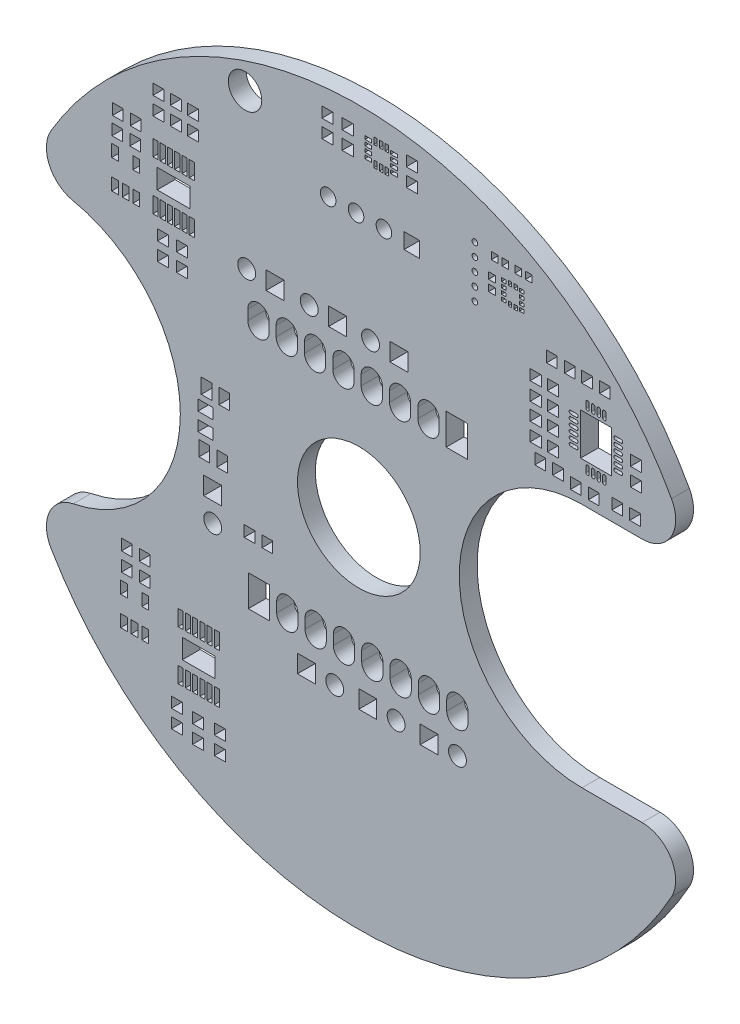
SolidWorks part; units mm, degrees
ref_plane "Plan de face" through (0, 0, 0) normal (0, 0, 1) x (1, 0, 0)
ref_plane "Plan de dessus" through (0, 0, 0) normal (0, 1, 0) x (1, 0, 0)
ref_plane "Plan de droite" through (0, 0, 0) normal (1, 0, 0) x (0, 0, -1)
sketch "Model" plane through (0, 0, 0) normal (0, 0, 1) x (1, 0, 0)
  line L0 (14.8, 23.5) -> (14.8, 23.2)
  line L1 (14.8, 23.2) -> (14.4, 23.2)
  line L2 (14.4, 23.2) -> (14.4, 23.5)
  line L3 (14.4, 23.5) -> (14.8, 23.5)
  line L4 (14.8, 24) -> (14.8, 23.7)
  line L5 (14.8, 23.7) -> (14.4, 23.7)
  line L6 (14.4, 23.7) -> (14.4, 24)
  line L7 (14.4, 24) -> (14.8, 24)
  line L8 (14.8, 24.5) -> (14.8, 24.2)
  line L9 (14.8, 24.2) -> (14.4, 24.2)
  line L10 (14.4, 24.2) -> (14.4, 24.5)
  line L11 (14.4, 24.5) -> (14.8, 24.5)
  line L12 (14.8, 25) -> (14.8, 24.7)
  line L13 (14.8, 24.7) -> (14.4, 24.7)
  line L14 (14.4, 24.7) -> (14.4, 25)
  line L15 (14.4, 25) -> (14.8, 25)
  line L16 (13.9, 25.1) -> (14.2, 25.1)
  line L17 (14.2, 25.1) -> (14.2, 24.7)
  line L18 (14.2, 24.7) -> (13.9, 24.7)
  line L19 (13.9, 24.7) -> (13.9, 25.1)
  line L20 (13.4, 25.1) -> (13.7, 25.1)
  line L21 (13.7, 25.1) -> (13.7, 24.7)
  line L22 (13.7, 24.7) -> (13.4, 24.7)
  line L23 (13.4, 24.7) -> (13.4, 25.1)
  line L24 (13.2, 25) -> (13.2, 24.7)
  line L25 (13.2, 24.7) -> (12.8, 24.7)
  line L26 (12.8, 24.7) -> (12.8, 25)
  line L27 (12.8, 25) -> (13.2, 25)
  line L28 (13.2, 24.5) -> (13.2, 24.2)
  line L29 (13.2, 24.2) -> (12.8, 24.2)
  line L30 (12.8, 24.2) -> (12.8, 24.5)
  line L31 (12.8, 24.5) -> (13.2, 24.5)
  line L32 (13.2, 24) -> (13.2, 23.7)
  line L33 (13.2, 23.7) -> (12.8, 23.7)
  line L34 (12.8, 23.7) -> (12.8, 24)
  line L35 (12.8, 24) -> (13.2, 24)
  line L36 (13.2, 23.5) -> (13.2, 23.2)
  line L37 (13.2, 23.2) -> (12.8, 23.2)
  line L38 (12.8, 23.2) -> (12.8, 23.5)
  line L39 (12.8, 23.5) -> (13.2, 23.5)
  line L40 (13.4, 23.5) -> (13.7, 23.5)
  line L41 (13.7, 23.5) -> (13.7, 23.1)
  line L42 (13.7, 23.1) -> (13.4, 23.1)
  line L43 (13.4, 23.1) -> (13.4, 23.5)
  line L44 (13.9, 23.5) -> (14.2, 23.5)
  line L45 (14.2, 23.5) -> (14.2, 23.1)
  line L46 (14.2, 23.1) -> (13.9, 23.1)
  line L47 (13.9, 23.1) -> (13.9, 23.5)
  line L48 (14.565, 25.93) -> (13.975, 25.93)
  line L49 (13.975, 25.93) -> (13.975, 26.57)
  line L50 (13.975, 26.57) -> (14.565, 26.57)
  line L51 (14.565, 26.57) -> (14.565, 25.93)
  line L52 (15.525, 25.93) -> (14.935, 25.93)
  line L53 (14.935, 25.93) -> (14.935, 26.57)
  line L54 (14.935, 26.57) -> (15.525, 26.57)
  line L55 (15.525, 26.57) -> (15.525, 25.93)
  line L56 (12.835, 26.57) -> (13.425, 26.57)
  line L57 (13.425, 26.57) -> (13.425, 25.93)
  line L58 (13.425, 25.93) -> (12.835, 25.93)
  line L59 (12.835, 25.93) -> (12.835, 26.57)
  line L60 (11.875, 26.57) -> (12.465, 26.57)
  line L61 (12.465, 26.57) -> (12.465, 25.93)
  line L62 (12.465, 25.93) -> (11.875, 25.93)
  line L63 (11.875, 25.93) -> (11.875, 26.57)
  line L64 (11.63, 24.285) -> (11.63, 24.875)
  line L65 (11.63, 24.875) -> (12.27, 24.875)
  line L66 (12.27, 24.875) -> (12.27, 24.285)
  line L67 (12.27, 24.285) -> (11.63, 24.285)
  line L68 (11.63, 23.325) -> (11.63, 23.915)
  line L69 (11.63, 23.915) -> (12.27, 23.915)
  line L70 (12.27, 23.915) -> (12.27, 23.325)
  line L71 (12.27, 23.325) -> (11.63, 23.325)
  line L72 (-12.725, -1.125) -> (-11.775, -1.125)
  line L73 (-11.775, -1.125) -> (-11.775, -2.475)
  line L74 (-11.775, -2.475) -> (-12.725, -2.475)
  line L75 (-12.725, -2.475) -> (-12.725, -1.125)
  line L76 (-14.325, -1.125) -> (-13.375, -1.125)
  line L77 (-13.375, -1.125) -> (-13.375, -2.475)
  line L78 (-13.375, -2.475) -> (-14.325, -2.475)
  line L79 (-14.325, -2.475) -> (-14.325, -1.125)
  line L80 (-12.525, 3.825) -> (-11.575, 3.825)
  line L81 (-11.575, 3.825) -> (-11.575, 2.475)
  line L82 (-11.575, 2.475) -> (-12.525, 2.475)
  line L83 (-12.525, 2.475) -> (-12.525, 3.825)
  line L84 (-14.125, 3.825) -> (-13.175, 3.825)
  line L85 (-13.175, 3.825) -> (-13.175, 2.475)
  line L86 (-13.175, 2.475) -> (-14.125, 2.475)
  line L87 (-14.125, 2.475) -> (-14.125, 3.825)
  line L88 (-13.075, 0.375) -> (-13.075, -0.575)
  line L89 (-13.075, -0.575) -> (-14.425, -0.575)
  line L90 (-14.425, -0.575) -> (-14.425, 0.375)
  line L91 (-14.425, 0.375) -> (-13.075, 0.375)
  line L92 (-13.075, 1.975) -> (-13.075, 1.025)
  line L93 (-13.075, 1.025) -> (-14.425, 1.025)
  line L94 (-14.425, 1.025) -> (-14.425, 1.975)
  line L95 (-14.425, 1.975) -> (-13.075, 1.975)
  line L96 (-21.55, 14.25) -> (-22.15, 14.25)
  line L97 (-22.15, 14.25) -> (-22.15, 15.35)
  line L98 (-22.15, 15.35) -> (-21.55, 15.35)
  line L99 (-21.55, 15.35) -> (-21.55, 14.25)
  line L100 (-20.6, 14.25) -> (-21.2, 14.25)
  line L101 (-21.2, 14.25) -> (-21.2, 15.35)
  line L102 (-21.2, 15.35) -> (-20.6, 15.35)
  line L103 (-20.6, 15.35) -> (-20.6, 14.25)
  line L104 (-19.65, 14.25) -> (-20.25, 14.25)
  line L105 (-20.25, 14.25) -> (-20.25, 15.35)
  line L106 (-20.25, 15.35) -> (-19.65, 15.35)
  line L107 (-19.65, 15.35) -> (-19.65, 14.25)
  line L108 (-19.65, 16.85) -> (-20.25, 16.85)
  line L109 (-20.25, 16.85) -> (-20.25, 17.95)
  line L110 (-20.25, 17.95) -> (-19.65, 17.95)
  line L111 (-19.65, 17.95) -> (-19.65, 16.85)
  line L112 (-21.55, 16.85) -> (-22.15, 16.85)
  line L113 (-22.15, 16.85) -> (-22.15, 17.95)
  line L114 (-22.15, 17.95) -> (-21.55, 17.95)
  line L115 (-21.55, 17.95) -> (-21.55, 16.85)
  line L116 (-20.75, -19.25) -> (-21.35, -19.25)
  line L117 (-21.35, -19.25) -> (-21.35, -18.15)
  line L118 (-21.35, -18.15) -> (-20.75, -18.15)
  line L119 (-20.75, -18.15) -> (-20.75, -19.25)
  line L120 (-19.8, -19.25) -> (-20.4, -19.25)
  line L121 (-20.4, -19.25) -> (-20.4, -18.15)
  line L122 (-20.4, -18.15) -> (-19.8, -18.15)
  line L123 (-19.8, -18.15) -> (-19.8, -19.25)
  line L124 (-18.85, -19.25) -> (-19.45, -19.25)
  line L125 (-19.45, -19.25) -> (-19.45, -18.15)
  line L126 (-19.45, -18.15) -> (-18.85, -18.15)
  line L127 (-18.85, -18.15) -> (-18.85, -19.25)
  line L128 (-18.85, -16.65) -> (-19.45, -16.65)
  line L129 (-19.45, -16.65) -> (-19.45, -15.55)
  line L130 (-19.45, -15.55) -> (-18.85, -15.55)
  line L131 (-18.85, -15.55) -> (-18.85, -16.65)
  line L132 (-20.75, -16.65) -> (-21.35, -16.65)
  line L133 (-21.35, -16.65) -> (-21.35, -15.55)
  line L134 (-21.35, -15.55) -> (-20.75, -15.55)
  line L135 (-20.75, -15.55) -> (-20.75, -16.65)
  line L136 (-18, 15.7505) -> (-18, 14.3255)
  line L137 (-18, 14.3255) -> (-18.45, 14.3255)
  line L138 (-18.45, 14.3255) -> (-18.45, 15.7505)
  line L139 (-18.45, 15.7505) -> (-18, 15.7505)
  line L140 (-17.35, 15.7505) -> (-17.35, 14.3255)
  line L141 (-17.35, 14.3255) -> (-17.8, 14.3255)
  line L142 (-17.8, 14.3255) -> (-17.8, 15.7505)
  line L143 (-17.8, 15.7505) -> (-17.35, 15.7505)
  line L144 (-16.7, 15.7505) -> (-16.7, 14.3255)
  line L145 (-16.7, 14.3255) -> (-17.15, 14.3255)
  line L146 (-17.15, 14.3255) -> (-17.15, 15.7505)
  line L147 (-17.15, 15.7505) -> (-16.7, 15.7505)
  line L148 (-16.05, 15.7505) -> (-16.05, 14.3255)
  line L149 (-16.05, 14.3255) -> (-16.5, 14.3255)
  line L150 (-16.5, 14.3255) -> (-16.5, 15.7505)
  line L151 (-16.5, 15.7505) -> (-16.05, 15.7505)
  line L152 (-15.4, 15.7505) -> (-15.4, 14.3255)
  line L153 (-15.4, 14.3255) -> (-15.85, 14.3255)
  line L154 (-15.85, 14.3255) -> (-15.85, 15.7505)
  line L155 (-15.85, 15.7505) -> (-15.4, 15.7505)
  line L156 (-14.75, 15.7505) -> (-14.75, 14.3255)
  line L157 (-14.75, 14.3255) -> (-15.2, 14.3255)
  line L158 (-15.2, 14.3255) -> (-15.2, 15.7505)
  line L159 (-15.2, 15.7505) -> (-14.75, 15.7505)
  line L160 (-14.75, 20.1745) -> (-14.75, 18.7495)
  line L161 (-14.75, 18.7495) -> (-15.2, 18.7495)
  line L162 (-15.2, 18.7495) -> (-15.2, 20.1745)
  line L163 (-15.2, 20.1745) -> (-14.75, 20.1745)
  line L164 (-15.4, 20.1745) -> (-15.4, 18.7495)
  line L165 (-15.4, 18.7495) -> (-15.85, 18.7495)
  line L166 (-15.85, 18.7495) -> (-15.85, 20.1745)
  line L167 (-15.85, 20.1745) -> (-15.4, 20.1745)
  line L168 (-16.05, 20.1745) -> (-16.05, 18.7495)
  line L169 (-16.05, 18.7495) -> (-16.5, 18.7495)
  line L170 (-16.5, 18.7495) -> (-16.5, 20.1745)
  line L171 (-16.5, 20.1745) -> (-16.05, 20.1745)
  line L172 (-16.7, 20.1745) -> (-16.7, 18.7495)
  line L173 (-16.7, 18.7495) -> (-17.15, 18.7495)
  line L174 (-17.15, 18.7495) -> (-17.15, 20.1745)
  line L175 (-17.15, 20.1745) -> (-16.7, 20.1745)
  line L176 (-17.35, 20.1745) -> (-17.35, 18.7495)
  line L177 (-17.35, 18.7495) -> (-17.8, 18.7495)
  line L178 (-17.8, 18.7495) -> (-17.8, 20.1745)
  line L179 (-17.8, 20.1745) -> (-17.35, 20.1745)
  line L180 (-18, 20.1745) -> (-18, 18.7495)
  line L181 (-18, 18.7495) -> (-18.45, 18.7495)
  line L182 (-18.45, 18.7495) -> (-18.45, 20.1745)
  line L183 (-18.45, 20.1745) -> (-18, 20.1745)
  line L184 (-18.0735, 18.1265) -> (-15.1265, 18.1265)
  line L185 (-15.1265, 18.1265) -> (-15.1265, 16.3735)
  line L186 (-15.1265, 16.3735) -> (-18.0735, 16.3735)
  line L187 (-18.0735, 16.3735) -> (-18.0735, 18.1265)
  line L188 (-12.95, -16.6005) -> (-12.95, -15.1755)
  line L189 (-12.95, -15.1755) -> (-12.5, -15.1755)
  line L190 (-12.5, -15.1755) -> (-12.5, -16.6005)
  line L191 (-12.5, -16.6005) -> (-12.95, -16.6005)
  line L192 (-13.6, -16.6005) -> (-13.6, -15.1755)
  line L193 (-13.6, -15.1755) -> (-13.15, -15.1755)
  line L194 (-13.15, -15.1755) -> (-13.15, -16.6005)
  line L195 (-13.15, -16.6005) -> (-13.6, -16.6005)
  line L196 (-14.25, -16.6005) -> (-14.25, -15.1755)
  line L197 (-14.25, -15.1755) -> (-13.8, -15.1755)
  line L198 (-13.8, -15.1755) -> (-13.8, -16.6005)
  line L199 (-13.8, -16.6005) -> (-14.25, -16.6005)
  line L200 (-14.9, -16.6005) -> (-14.9, -15.1755)
  line L201 (-14.9, -15.1755) -> (-14.45, -15.1755)
  line L202 (-14.45, -15.1755) -> (-14.45, -16.6005)
  line L203 (-14.45, -16.6005) -> (-14.9, -16.6005)
  line L204 (-15.55, -16.6005) -> (-15.55, -15.1755)
  line L205 (-15.55, -15.1755) -> (-15.1, -15.1755)
  line L206 (-15.1, -15.1755) -> (-15.1, -16.6005)
  line L207 (-15.1, -16.6005) -> (-15.55, -16.6005)
  line L208 (-16.2, -16.6005) -> (-16.2, -15.1755)
  line L209 (-16.2, -15.1755) -> (-15.75, -15.1755)
  line L210 (-15.75, -15.1755) -> (-15.75, -16.6005)
  line L211 (-15.75, -16.6005) -> (-16.2, -16.6005)
  line L212 (-16.2, -21.0245) -> (-16.2, -19.5995)
  line L213 (-16.2, -19.5995) -> (-15.75, -19.5995)
  line L214 (-15.75, -19.5995) -> (-15.75, -21.0245)
  line L215 (-15.75, -21.0245) -> (-16.2, -21.0245)
  line L216 (-15.55, -21.0245) -> (-15.55, -19.5995)
  line L217 (-15.55, -19.5995) -> (-15.1, -19.5995)
  line L218 (-15.1, -19.5995) -> (-15.1, -21.0245)
  line L219 (-15.1, -21.0245) -> (-15.55, -21.0245)
  line L220 (-14.9, -21.0245) -> (-14.9, -19.5995)
  line L221 (-14.9, -19.5995) -> (-14.45, -19.5995)
  line L222 (-14.45, -19.5995) -> (-14.45, -21.0245)
  line L223 (-14.45, -21.0245) -> (-14.9, -21.0245)
  line L224 (-14.25, -21.0245) -> (-14.25, -19.5995)
  line L225 (-14.25, -19.5995) -> (-13.8, -19.5995)
  line L226 (-13.8, -19.5995) -> (-13.8, -21.0245)
  line L227 (-13.8, -21.0245) -> (-14.25, -21.0245)
  line L228 (-13.6, -21.0245) -> (-13.6, -19.5995)
  line L229 (-13.6, -19.5995) -> (-13.15, -19.5995)
  line L230 (-13.15, -19.5995) -> (-13.15, -21.0245)
  line L231 (-13.15, -21.0245) -> (-13.6, -21.0245)
  line L232 (-12.95, -21.0245) -> (-12.95, -19.5995)
  line L233 (-12.95, -19.5995) -> (-12.5, -19.5995)
  line L234 (-12.5, -19.5995) -> (-12.5, -21.0245)
  line L235 (-12.5, -21.0245) -> (-12.95, -21.0245)
  line L236 (-12.8765, -18.9765) -> (-15.8235, -18.9765)
  line L237 (-15.8235, -18.9765) -> (-15.8235, -17.2235)
  line L238 (-15.8235, -17.2235) -> (-12.8765, -17.2235)
  line L239 (-12.8765, -17.2235) -> (-12.8765, -18.9765)
  line L240 (9.7325, 12.147) -> (9.7325, 9.353)
  line L241 (9.7325, 9.353) -> (7.8275, 9.353)
  line L242 (7.8275, 9.353) -> (7.8275, 12.147)
  line L243 (7.8275, 12.147) -> (9.7325, 12.147)
  line L244 (5.2875, 10.3055) -> (5.2875, 11.1945)
  line L245 (7.1925, 11.1945) -> (7.1925, 10.3055)
  line L246 (2.7475, 10.3055) -> (2.7475, 11.1945)
  line L247 (4.6525, 11.1945) -> (4.6525, 10.3055)
  line L248 (0.2075, 10.3055) -> (0.2075, 11.1945)
  line L249 (2.1125, 11.1945) -> (2.1125, 10.3055)
  line L250 (-2.3325, 10.3055) -> (-2.3325, 11.1945)
  line L251 (-0.4275, 11.1945) -> (-0.4275, 10.3055)
  line L252 (-4.8725, 10.3055) -> (-4.8725, 11.1945)
  line L253 (-2.9675, 11.1945) -> (-2.9675, 10.3055)
  line L254 (-7.4125, 10.3055) -> (-7.4125, 11.1945)
  line L255 (-5.5075, 11.1945) -> (-5.5075, 10.3055)
  line L256 (-9.9525, 10.3055) -> (-9.9525, 11.1945)
  line L257 (-8.0475, 11.1945) -> (-8.0475, 10.3055)
  line L258 (-9.9025, -12.047) -> (-9.9025, -9.253)
  line L259 (-9.9025, -9.253) -> (-7.9975, -9.253)
  line L260 (-7.9975, -9.253) -> (-7.9975, -12.047)
  line L261 (-7.9975, -12.047) -> (-9.9025, -12.047)
  line L262 (-5.4575, -10.2055) -> (-5.4575, -11.0945)
  line L263 (-7.3625, -11.0945) -> (-7.3625, -10.2055)
  line L264 (-2.9175, -10.2055) -> (-2.9175, -11.0945)
  line L265 (-4.8225, -11.0945) -> (-4.8225, -10.2055)
  line L266 (-0.3775, -10.2055) -> (-0.3775, -11.0945)
  line L267 (-2.2825, -11.0945) -> (-2.2825, -10.2055)
  line L268 (2.1625, -10.2055) -> (2.1625, -11.0945)
  line L269 (0.2575, -11.0945) -> (0.2575, -10.2055)
  line L270 (4.7025, -10.2055) -> (4.7025, -11.0945)
  line L271 (2.7975, -11.0945) -> (2.7975, -10.2055)
  line L272 (7.2425, -10.2055) -> (7.2425, -11.0945)
  line L273 (5.3375, -11.0945) -> (5.3375, -10.2055)
  line L274 (9.7825, -10.2055) -> (9.7825, -11.0945)
  line L275 (7.8775, -11.0945) -> (7.8775, -10.2055)
  line L276 (3.45, 28.4) -> (3.45, 28.1)
  line L277 (3.45, 28.1) -> (2.85, 28.1)
  line L278 (2.85, 28.1) -> (2.85, 28.4)
  line L279 (2.85, 28.4) -> (3.45, 28.4)
  line L280 (3.45, 28.9) -> (3.45, 28.6)
  line L281 (3.45, 28.6) -> (2.85, 28.6)
  line L282 (2.85, 28.6) -> (2.85, 28.9)
  line L283 (2.85, 28.9) -> (3.45, 28.9)
  line L284 (3.45, 29.4) -> (3.45, 29.1)
  line L285 (3.45, 29.1) -> (2.85, 29.1)
  line L286 (2.85, 29.1) -> (2.85, 29.4)
  line L287 (2.85, 29.4) -> (3.45, 29.4)
  line L288 (3.45, 29.9) -> (3.45, 29.6)
  line L289 (3.45, 29.6) -> (2.85, 29.6)
  line L290 (2.85, 29.6) -> (2.85, 29.9)
  line L291 (2.85, 29.9) -> (3.45, 29.9)
  line L292 (2.35, 30.2) -> (2.65, 30.2)
  line L293 (2.65, 30.2) -> (2.65, 29.6)
  line L294 (2.65, 29.6) -> (2.35, 29.6)
  line L295 (2.35, 29.6) -> (2.35, 30.2)
  line L296 (1.85, 30.2) -> (2.15, 30.2)
  line L297 (2.15, 30.2) -> (2.15, 29.6)
  line L298 (2.15, 29.6) -> (1.85, 29.6)
  line L299 (1.85, 29.6) -> (1.85, 30.2)
  line L300 (1.35, 30.2) -> (1.65, 30.2)
  line L301 (1.65, 30.2) -> (1.65, 29.6)
  line L302 (1.65, 29.6) -> (1.35, 29.6)
  line L303 (1.35, 29.6) -> (1.35, 30.2)
  line L304 (1.15, 29.9) -> (1.15, 29.6)
  line L305 (1.15, 29.6) -> (0.55, 29.6)
  line L306 (0.55, 29.6) -> (0.55, 29.9)
  line L307 (0.55, 29.9) -> (1.15, 29.9)
  line L308 (1.15, 29.4) -> (1.15, 29.1)
  line L309 (1.15, 29.1) -> (0.55, 29.1)
  line L310 (0.55, 29.1) -> (0.55, 29.4)
  line L311 (0.55, 29.4) -> (1.15, 29.4)
  line L312 (1.15, 28.9) -> (1.15, 28.6)
  line L313 (1.15, 28.6) -> (0.55, 28.6)
  line L314 (0.55, 28.6) -> (0.55, 28.9)
  line L315 (0.55, 28.9) -> (1.15, 28.9)
  line L316 (1.15, 28.4) -> (1.15, 28.1)
  line L317 (1.15, 28.1) -> (0.55, 28.1)
  line L318 (0.55, 28.1) -> (0.55, 28.4)
  line L319 (0.55, 28.4) -> (1.15, 28.4)
  line L320 (1.35, 28.4) -> (1.65, 28.4)
  line L321 (1.65, 28.4) -> (1.65, 27.8)
  line L322 (1.65, 27.8) -> (1.35, 27.8)
  line L323 (1.35, 27.8) -> (1.35, 28.4)
  line L324 (1.85, 28.4) -> (2.15, 28.4)
  line L325 (2.15, 28.4) -> (2.15, 27.8)
  line L326 (2.15, 27.8) -> (1.85, 27.8)
  line L327 (1.85, 27.8) -> (1.85, 28.4)
  line L328 (2.35, 28.4) -> (2.65, 28.4)
  line L329 (2.65, 28.4) -> (2.65, 27.8)
  line L330 (2.65, 27.8) -> (2.35, 27.8)
  line L331 (2.35, 27.8) -> (2.35, 28.4)
  line L332 (23, 15.3) -> (23.5, 15.3)
  line L333 (23.5, 15) -> (23, 15)
  line L334 (23, 15.8) -> (23.5, 15.8)
  line L335 (23.5, 15.5) -> (23, 15.5)
  line L336 (23, 16.3) -> (23.5, 16.3)
  line L337 (23.5, 16) -> (23, 16)
  line L338 (23, 16.8) -> (23.5, 16.8)
  line L339 (23.5, 16.5) -> (23, 16.5)
  line L340 (23, 17.3) -> (23.5, 17.3)
  line L341 (23.5, 17) -> (23, 17)
  line L342 (23, 17.8) -> (23.5, 17.8)
  line L343 (23.5, 17.5) -> (23, 17.5)
  line L344 (21.85, 18.65) -> (21.85, 19.15)
  line L345 (22.15, 19.15) -> (22.15, 18.65)
  line L346 (21.35, 18.65) -> (21.35, 19.15)
  line L347 (21.65, 19.15) -> (21.65, 18.65)
  line L348 (20.85, 18.65) -> (20.85, 19.15)
  line L349 (21.15, 19.15) -> (21.15, 18.65)
  line L350 (20.35, 18.65) -> (20.35, 19.15)
  line L351 (20.65, 19.15) -> (20.65, 18.65)
  line L352 (19, 17.8) -> (19.5, 17.8)
  line L353 (19.5, 17.5) -> (19, 17.5)
  line L354 (19, 17.3) -> (19.5, 17.3)
  line L355 (19.5, 17) -> (19, 17)
  line L356 (19, 16.8) -> (19.5, 16.8)
  line L357 (19.5, 16.5) -> (19, 16.5)
  line L358 (19, 16.3) -> (19.5, 16.3)
  line L359 (19.5, 16) -> (19, 16)
  line L360 (19, 15.8) -> (19.5, 15.8)
  line L361 (19.5, 15.5) -> (19, 15.5)
  line L362 (19, 15.3) -> (19.5, 15.3)
  line L363 (19.5, 15) -> (19, 15)
  line L364 (20.35, 13.65) -> (20.35, 14.15)
  line L365 (20.65, 14.15) -> (20.65, 13.65)
  line L366 (20.85, 13.65) -> (20.85, 14.15)
  line L367 (21.15, 14.15) -> (21.15, 13.65)
  line L368 (21.35, 13.65) -> (21.35, 14.15)
  line L369 (21.65, 14.15) -> (21.65, 13.65)
  line L370 (21.85, 13.65) -> (21.85, 14.15)
  line L371 (22.15, 14.15) -> (22.15, 13.65)
  line L372 (22.625, 18.275) -> (22.625, 14.525)
  line L373 (22.625, 14.525) -> (19.875, 14.525)
  line L374 (19.875, 14.525) -> (19.875, 18.275)
  line L375 (19.875, 18.275) -> (22.625, 18.275)
  line L376 (-9.325, -6.7) -> (-10.275, -6.7)
  line L377 (-10.275, -6.7) -> (-10.275, -5.7)
  line L378 (-10.275, -5.7) -> (-9.325, -5.7)
  line L379 (-9.325, -5.7) -> (-9.325, -6.7)
  line L380 (-7.725, -6.7) -> (-8.675, -6.7)
  line L381 (-8.675, -6.7) -> (-8.675, -5.7)
  line L382 (-8.675, -5.7) -> (-7.725, -5.7)
  line L383 (-7.725, -5.7) -> (-7.725, -6.7)
  line L384 (-21.125, 20.15) -> (-22.075, 20.15)
  line L385 (-22.075, 20.15) -> (-22.075, 21.15)
  line L386 (-22.075, 21.15) -> (-21.125, 21.15)
  line L387 (-21.125, 21.15) -> (-21.125, 20.15)
  line L388 (-19.525, 20.15) -> (-20.475, 20.15)
  line L389 (-20.475, 20.15) -> (-20.475, 21.15)
  line L390 (-20.475, 21.15) -> (-19.525, 21.15)
  line L391 (-19.525, 21.15) -> (-19.525, 20.15)
  line L392 (-20.325, -13.25) -> (-21.275, -13.25)
  line L393 (-21.275, -13.25) -> (-21.275, -12.25)
  line L394 (-21.275, -12.25) -> (-20.325, -12.25)
  line L395 (-20.325, -12.25) -> (-20.325, -13.25)
  line L396 (-18.725, -13.25) -> (-19.675, -13.25)
  line L397 (-19.675, -13.25) -> (-19.675, -12.25)
  line L398 (-19.675, -12.25) -> (-18.725, -12.25)
  line L399 (-18.725, -12.25) -> (-18.725, -13.25)
  line L400 (-21.175, 18.55) -> (-22.125, 18.55)
  line L401 (-22.125, 18.55) -> (-22.125, 19.55)
  line L402 (-22.125, 19.55) -> (-21.175, 19.55)
  line L403 (-21.175, 19.55) -> (-21.175, 18.55)
  line L404 (-19.575, 18.55) -> (-20.525, 18.55)
  line L405 (-20.525, 18.55) -> (-20.525, 19.55)
  line L406 (-20.525, 19.55) -> (-19.575, 19.55)
  line L407 (-19.575, 19.55) -> (-19.575, 18.55)
  line L408 (-20.325, -14.9) -> (-21.275, -14.9)
  line L409 (-21.275, -14.9) -> (-21.275, -13.9)
  line L410 (-21.275, -13.9) -> (-20.325, -13.9)
  line L411 (-20.325, -13.9) -> (-20.325, -14.9)
  line L412 (-18.725, -14.9) -> (-19.675, -14.9)
  line L413 (-19.675, -14.9) -> (-19.675, -13.9)
  line L414 (-19.675, -13.9) -> (-18.725, -13.9)
  line L415 (-18.725, -13.9) -> (-18.725, -14.9)
  line L416 (-18.45, 23.525) -> (-18.45, 24.475)
  line L417 (-18.45, 24.475) -> (-17.45, 24.475)
  line L418 (-17.45, 24.475) -> (-17.45, 23.525)
  line L419 (-17.45, 23.525) -> (-18.45, 23.525)
  line L420 (-18.45, 21.925) -> (-18.45, 22.875)
  line L421 (-18.45, 22.875) -> (-17.45, 22.875)
  line L422 (-17.45, 22.875) -> (-17.45, 21.925)
  line L423 (-17.45, 21.925) -> (-18.45, 21.925)
  line L424 (20.925, 20.4) -> (19.975, 20.4)
  line L425 (19.975, 20.4) -> (19.975, 21.4)
  line L426 (19.975, 21.4) -> (20.925, 21.4)
  line L427 (20.925, 21.4) -> (20.925, 20.4)
  line L428 (22.525, 20.4) -> (21.575, 20.4)
  line L429 (21.575, 20.4) -> (21.575, 21.4)
  line L430 (21.575, 21.4) -> (22.525, 21.4)
  line L431 (22.525, 21.4) -> (22.525, 20.4)
  line L432 (-15.9, 22.875) -> (-15.9, 21.925)
  line L433 (-15.9, 21.925) -> (-16.9, 21.925)
  line L434 (-16.9, 21.925) -> (-16.9, 22.875)
  line L435 (-16.9, 22.875) -> (-15.9, 22.875)
  line L436 (-15.9, 24.475) -> (-15.9, 23.525)
  line L437 (-15.9, 23.525) -> (-16.9, 23.525)
  line L438 (-16.9, 23.525) -> (-16.9, 24.475)
  line L439 (-16.9, 24.475) -> (-15.9, 24.475)
  line L440 (-14.9, -23.475) -> (-14.9, -22.525)
  line L441 (-14.9, -22.525) -> (-13.9, -22.525)
  line L442 (-13.9, -22.525) -> (-13.9, -23.475)
  line L443 (-13.9, -23.475) -> (-14.9, -23.475)
  line L444 (-14.9, -25.075) -> (-14.9, -24.125)
  line L445 (-14.9, -24.125) -> (-13.9, -24.125)
  line L446 (-13.9, -24.125) -> (-13.9, -25.075)
  line L447 (-13.9, -25.075) -> (-14.9, -25.075)
  line L448 (-18.05, 12.425) -> (-18.05, 13.375)
  line L449 (-18.05, 13.375) -> (-17.05, 13.375)
  line L450 (-17.05, 13.375) -> (-17.05, 12.425)
  line L451 (-17.05, 12.425) -> (-18.05, 12.425)
  line L452 (-18.05, 10.825) -> (-18.05, 11.775)
  line L453 (-18.05, 11.775) -> (-17.05, 11.775)
  line L454 (-17.05, 11.775) -> (-17.05, 10.825)
  line L455 (-17.05, 10.825) -> (-18.05, 10.825)
  line L456 (-15.35, 11.775) -> (-15.35, 10.825)
  line L457 (-15.35, 10.825) -> (-16.35, 10.825)
  line L458 (-16.35, 10.825) -> (-16.35, 11.775)
  line L459 (-16.35, 11.775) -> (-15.35, 11.775)
  line L460 (-15.35, 13.375) -> (-15.35, 12.425)
  line L461 (-15.35, 12.425) -> (-16.35, 12.425)
  line L462 (-16.35, 12.425) -> (-16.35, 13.375)
  line L463 (-16.35, 13.375) -> (-15.35, 13.375)
  line L464 (-15.35, 23.525) -> (-15.35, 24.475)
  line L465 (-15.35, 24.475) -> (-14.35, 24.475)
  line L466 (-14.35, 24.475) -> (-14.35, 23.525)
  line L467 (-14.35, 23.525) -> (-15.35, 23.525)
  line L468 (-15.35, 21.925) -> (-15.35, 22.875)
  line L469 (-15.35, 22.875) -> (-14.35, 22.875)
  line L470 (-14.35, 22.875) -> (-14.35, 21.925)
  line L471 (-14.35, 21.925) -> (-15.35, 21.925)
  line L472 (4.25, 29.325) -> (4.25, 30.275)
  line L473 (4.25, 30.275) -> (5.25, 30.275)
  line L474 (5.25, 30.275) -> (5.25, 29.325)
  line L475 (5.25, 29.325) -> (4.25, 29.325)
  line L476 (4.25, 27.725) -> (4.25, 28.675)
  line L477 (4.25, 28.675) -> (5.25, 28.675)
  line L478 (5.25, 28.675) -> (5.25, 27.725)
  line L479 (5.25, 27.725) -> (4.25, 27.725)
  line L480 (-2.3, 28.675) -> (-2.3, 27.725)
  line L481 (-2.3, 27.725) -> (-3.3, 27.725)
  line L482 (-3.3, 27.725) -> (-3.3, 28.675)
  line L483 (-3.3, 28.675) -> (-2.3, 28.675)
  line L484 (-2.3, 30.275) -> (-2.3, 29.325)
  line L485 (-2.3, 29.325) -> (-3.3, 29.325)
  line L486 (-3.3, 29.325) -> (-3.3, 30.275)
  line L487 (-3.3, 30.275) -> (-2.3, 30.275)
  line L488 (-0.5, 28.675) -> (-0.5, 27.725)
  line L489 (-0.5, 27.725) -> (-1.5, 27.725)
  line L490 (-1.5, 27.725) -> (-1.5, 28.675)
  line L491 (-1.5, 28.675) -> (-0.5, 28.675)
  line L492 (-0.5, 30.275) -> (-0.5, 29.325)
  line L493 (-0.5, 29.325) -> (-1.5, 29.325)
  line L494 (-1.5, 29.325) -> (-1.5, 30.275)
  line L495 (-1.5, 30.275) -> (-0.5, 30.275)
  line L496 (16.725, 11.95) -> (15.775, 11.95)
  line L497 (15.775, 11.95) -> (15.775, 12.95)
  line L498 (15.775, 12.95) -> (16.725, 12.95)
  line L499 (16.725, 12.95) -> (16.725, 11.95)
  line L500 (18.325, 11.95) -> (17.375, 11.95)
  line L501 (17.375, 11.95) -> (17.375, 12.95)
  line L502 (17.375, 12.95) -> (18.325, 12.95)
  line L503 (18.325, 12.95) -> (18.325, 11.95)
  line L504 (19.925, 11.65) -> (18.975, 11.65)
  line L505 (18.975, 11.65) -> (18.975, 12.65)
  line L506 (18.975, 12.65) -> (19.925, 12.65)
  line L507 (19.925, 12.65) -> (19.925, 11.65)
  line L508 (21.525, 11.65) -> (20.575, 11.65)
  line L509 (20.575, 11.65) -> (20.575, 12.65)
  line L510 (20.575, 12.65) -> (21.525, 12.65)
  line L511 (21.525, 12.65) -> (21.525, 11.65)
  line L512 (17.775, 20.4) -> (16.825, 20.4)
  line L513 (16.825, 20.4) -> (16.825, 21.4)
  line L514 (16.825, 21.4) -> (17.775, 21.4)
  line L515 (17.775, 21.4) -> (17.775, 20.4)
  line L516 (19.375, 20.4) -> (18.425, 20.4)
  line L517 (18.425, 20.4) -> (18.425, 21.4)
  line L518 (18.425, 21.4) -> (19.375, 21.4)
  line L519 (19.375, 21.4) -> (19.375, 20.4)
  line L520 (25.35, 15.475) -> (25.35, 14.525)
  line L521 (25.35, 14.525) -> (24.35, 14.525)
  line L522 (24.35, 14.525) -> (24.35, 15.475)
  line L523 (24.35, 15.475) -> (25.35, 15.475)
  line L524 (25.35, 17.075) -> (25.35, 16.125)
  line L525 (25.35, 16.125) -> (24.35, 16.125)
  line L526 (24.35, 16.125) -> (24.35, 17.075)
  line L527 (24.35, 17.075) -> (25.35, 17.075)
  line L528 (24.275, 12.9) -> (25.225, 12.9)
  line L529 (25.225, 12.9) -> (25.225, 11.9)
  line L530 (25.225, 11.9) -> (24.275, 11.9)
  line L531 (24.275, 11.9) -> (24.275, 12.9)
  line L532 (22.675, 12.9) -> (23.625, 12.9)
  line L533 (23.625, 12.9) -> (23.625, 11.9)
  line L534 (23.625, 11.9) -> (22.675, 11.9)
  line L535 (22.675, 11.9) -> (22.675, 12.9)
  line L536 (16.35, 14.475) -> (16.35, 13.525)
  line L537 (16.35, 13.525) -> (15.35, 13.525)
  line L538 (15.35, 13.525) -> (15.35, 14.475)
  line L539 (15.35, 14.475) -> (16.35, 14.475)
  line L540 (16.35, 16.075) -> (16.35, 15.125)
  line L541 (16.35, 15.125) -> (15.35, 15.125)
  line L542 (15.35, 15.125) -> (15.35, 16.075)
  line L543 (15.35, 16.075) -> (16.35, 16.075)
  line L544 (17.9, 14.475) -> (17.9, 13.525)
  line L545 (17.9, 13.525) -> (16.9, 13.525)
  line L546 (16.9, 13.525) -> (16.9, 14.475)
  line L547 (16.9, 14.475) -> (17.9, 14.475)
  line L548 (17.9, 16.075) -> (17.9, 15.125)
  line L549 (17.9, 15.125) -> (16.9, 15.125)
  line L550 (16.9, 15.125) -> (16.9, 16.075)
  line L551 (16.9, 16.075) -> (17.9, 16.075)
  line L552 (16.35, 17.625) -> (16.35, 16.675)
  line L553 (16.35, 16.675) -> (15.35, 16.675)
  line L554 (15.35, 16.675) -> (15.35, 17.625)
  line L555 (15.35, 17.625) -> (16.35, 17.625)
  line L556 (16.35, 19.225) -> (16.35, 18.275)
  line L557 (16.35, 18.275) -> (15.35, 18.275)
  line L558 (15.35, 18.275) -> (15.35, 19.225)
  line L559 (15.35, 19.225) -> (16.35, 19.225)
  line L560 (17.9, 17.625) -> (17.9, 16.675)
  line L561 (17.9, 16.675) -> (16.9, 16.675)
  line L562 (16.9, 16.675) -> (16.9, 17.625)
  line L563 (16.9, 17.625) -> (17.9, 17.625)
  line L564 (17.9, 19.225) -> (17.9, 18.275)
  line L565 (17.9, 18.275) -> (16.9, 18.275)
  line L566 (16.9, 18.275) -> (16.9, 19.225)
  line L567 (16.9, 19.225) -> (17.9, 19.225)
  line L568 (-16.8, -23.225) -> (-16.8, -22.275)
  line L569 (-16.8, -22.275) -> (-15.8, -22.275)
  line L570 (-15.8, -22.275) -> (-15.8, -23.225)
  line L571 (-15.8, -23.225) -> (-16.8, -23.225)
  line L572 (-16.8, -24.825) -> (-16.8, -23.875)
  line L573 (-16.8, -23.875) -> (-15.8, -23.875)
  line L574 (-15.8, -23.875) -> (-15.8, -24.825)
  line L575 (-15.8, -24.825) -> (-16.8, -24.825)
  line L576 (-11.95, -24.025) -> (-11.95, -24.975)
  line L577 (-11.95, -24.975) -> (-12.95, -24.975)
  line L578 (-12.95, -24.975) -> (-12.95, -24.025)
  line L579 (-12.95, -24.025) -> (-11.95, -24.025)
  line L580 (-11.95, -22.425) -> (-11.95, -23.375)
  line L581 (-11.95, -23.375) -> (-12.95, -23.375)
  line L582 (-12.95, -23.375) -> (-12.95, -22.425)
  line L583 (-12.95, -22.425) -> (-11.95, -22.425)
  line L584 (5.45, 24.2) -> (5.45, 22.8)
  line L585 (5.45, 22.8) -> (4.05, 22.8)
  line L586 (4.05, 22.8) -> (4.05, 24.2)
  line L587 (4.05, 24.2) -> (5.45, 24.2)
  line L588 (-6.71, 15.05) -> (-6.71, 13.45)
  line L589 (-6.71, 13.45) -> (-8.31, 13.45)
  line L590 (-8.31, 13.45) -> (-8.31, 15.05)
  line L591 (-8.31, 15.05) -> (-6.71, 15.05)
  line L592 (-1.11, 15.05) -> (-1.11, 13.45)
  line L593 (-1.11, 13.45) -> (-2.71, 13.45)
  line L594 (-2.71, 13.45) -> (-2.71, 15.05)
  line L595 (-2.71, 15.05) -> (-1.11, 15.05)
  line L596 (4.39, 15.05) -> (4.39, 13.45)
  line L597 (4.39, 13.45) -> (2.79, 13.45)
  line L598 (2.79, 13.45) -> (2.79, 15.05)
  line L599 (2.79, 15.05) -> (4.39, 15.05)
  line L600 (5.5, -14.9) -> (5.5, -13.3)
  line L601 (5.5, -13.3) -> (7.1, -13.3)
  line L602 (7.1, -13.3) -> (7.1, -14.9)
  line L603 (7.1, -14.9) -> (5.5, -14.9)
  line L604 (0, -14.9) -> (0, -13.3)
  line L605 (0, -13.3) -> (1.6, -13.3)
  line L606 (1.6, -13.3) -> (1.6, -14.9)
  line L607 (1.6, -14.9) -> (0, -14.9)
  line L608 (-5.5, -14.9) -> (-5.5, -13.3)
  line L609 (-5.5, -13.3) -> (-3.9, -13.3)
  line L610 (-3.9, -13.3) -> (-3.9, -14.9)
  line L611 (-3.9, -14.9) -> (-5.5, -14.9)
  line L612 (-13.9, -3.68) -> (-12.3, -3.68)
  line L613 (-12.3, -3.68) -> (-12.3, -5.28)
  line L614 (-12.3, -5.28) -> (-13.9, -5.28)
  line L615 (-13.9, -5.28) -> (-13.9, -3.68)
  line L616 (25.3969, -11) -> (20, -11)
  line L617 (20, 11) -> (25.3969, 11)
  circle A0 centre (0, 0) radius 8.5 construction
  circle A1 centre (10.4, 21.95) radius 0.254
  circle A2 centre (10.4, 23.1) radius 0.254
  circle A3 centre (10.4, 24.25) radius 0.254
  circle A4 centre (10.4, 25.4) radius 0.254
  circle A5 centre (10.4, 26.55) radius 0.254
  circle A6 centre (-10.2, 28) radius 1.5
  circle A7 centre (2.25, 23.5) radius 0.7
  circle A8 centre (-0.25, 23.5) radius 0.7
  circle A9 centre (-2.75, 23.5) radius 0.7
  circle A10 centre (-10.05, 14.25) radius 0.8
  circle A11 centre (-4.45, 14.25) radius 0.8
  circle A12 centre (1.05, 14.25) radius 0.8
  circle A13 centre (8.84, -14.1) radius 0.8
  circle A14 centre (3.34, -14.1) radius 0.8
  circle A15 centre (-2.16, -14.1) radius 0.8
  circle A16 centre (-13.1, -7.02) radius 0.8
  arc A17 (7.1925, 11.1945) -> (5.2875, 11.1945) centre (6.24, 11.1945) ccw
  arc A18 (5.2875, 10.3055) -> (7.1925, 10.3055) centre (6.24, 10.3055) ccw
  arc A19 (4.6525, 11.1945) -> (2.7475, 11.1945) centre (3.7, 11.1945) ccw
  arc A20 (2.7475, 10.3055) -> (4.6525, 10.3055) centre (3.7, 10.3055) ccw
  arc A21 (2.1125, 11.1945) -> (0.2075, 11.1945) centre (1.16, 11.1945) ccw
  arc A22 (0.2075, 10.3055) -> (2.1125, 10.3055) centre (1.16, 10.3055) ccw
  arc A23 (-0.4275, 11.1945) -> (-2.3325, 11.1945) centre (-1.38, 11.1945) ccw
  arc A24 (-2.3325, 10.3055) -> (-0.4275, 10.3055) centre (-1.38, 10.3055) ccw
  arc A25 (-2.9675, 11.1945) -> (-4.8725, 11.1945) centre (-3.92, 11.1945) ccw
  arc A26 (-4.8725, 10.3055) -> (-2.9675, 10.3055) centre (-3.92, 10.3055) ccw
  arc A27 (-5.5075, 11.1945) -> (-7.4125, 11.1945) centre (-6.46, 11.1945) ccw
  arc A28 (-7.4125, 10.3055) -> (-5.5075, 10.3055) centre (-6.46, 10.3055) ccw
  arc A29 (-8.0475, 11.1945) -> (-9.9525, 11.1945) centre (-9, 11.1945) ccw
  arc A30 (-9.9525, 10.3055) -> (-8.0475, 10.3055) centre (-9, 10.3055) ccw
  arc A31 (-7.3625, -11.0945) -> (-5.4575, -11.0945) centre (-6.41, -11.0945) ccw
  arc A32 (-5.4575, -10.2055) -> (-7.3625, -10.2055) centre (-6.41, -10.2055) ccw
  arc A33 (-4.8225, -11.0945) -> (-2.9175, -11.0945) centre (-3.87, -11.0945) ccw
  arc A34 (-2.9175, -10.2055) -> (-4.8225, -10.2055) centre (-3.87, -10.2055) ccw
  arc A35 (-2.2825, -11.0945) -> (-0.3775, -11.0945) centre (-1.33, -11.0945) ccw
  arc A36 (-0.3775, -10.2055) -> (-2.2825, -10.2055) centre (-1.33, -10.2055) ccw
  arc A37 (0.2575, -11.0945) -> (2.1625, -11.0945) centre (1.21, -11.0945) ccw
  arc A38 (2.1625, -10.2055) -> (0.2575, -10.2055) centre (1.21, -10.2055) ccw
  arc A39 (2.7975, -11.0945) -> (4.7025, -11.0945) centre (3.75, -11.0945) ccw
  arc A40 (4.7025, -10.2055) -> (2.7975, -10.2055) centre (3.75, -10.2055) ccw
  arc A41 (5.3375, -11.0945) -> (7.2425, -11.0945) centre (6.29, -11.0945) ccw
  arc A42 (7.2425, -10.2055) -> (5.3375, -10.2055) centre (6.29, -10.2055) ccw
  arc A43 (7.8775, -11.0945) -> (9.7825, -11.0945) centre (8.83, -11.0945) ccw
  arc A44 (9.7825, -10.2055) -> (7.8775, -10.2055) centre (8.83, -10.2055) ccw
  arc A45 (23.5, 15) -> (23.5, 15.3) centre (23.5, 15.15) ccw
  arc A46 (23, 15.3) -> (23, 15) centre (23, 15.15) ccw
  arc A47 (23.5, 15.5) -> (23.5, 15.8) centre (23.5, 15.65) ccw
  arc A48 (23, 15.8) -> (23, 15.5) centre (23, 15.65) ccw
  arc A49 (23.5, 16) -> (23.5, 16.3) centre (23.5, 16.15) ccw
  arc A50 (23, 16.3) -> (23, 16) centre (23, 16.15) ccw
  arc A51 (23.5, 16.5) -> (23.5, 16.8) centre (23.5, 16.65) ccw
  arc A52 (23, 16.8) -> (23, 16.5) centre (23, 16.65) ccw
  arc A53 (23.5, 17) -> (23.5, 17.3) centre (23.5, 17.15) ccw
  arc A54 (23, 17.3) -> (23, 17) centre (23, 17.15) ccw
  arc A55 (23.5, 17.5) -> (23.5, 17.8) centre (23.5, 17.65) ccw
  arc A56 (23, 17.8) -> (23, 17.5) centre (23, 17.65) ccw
  arc A57 (22.15, 19.15) -> (21.85, 19.15) centre (22, 19.15) ccw
  arc A58 (21.85, 18.65) -> (22.15, 18.65) centre (22, 18.65) ccw
  arc A59 (21.65, 19.15) -> (21.35, 19.15) centre (21.5, 19.15) ccw
  arc A60 (21.35, 18.65) -> (21.65, 18.65) centre (21.5, 18.65) ccw
  arc A61 (21.15, 19.15) -> (20.85, 19.15) centre (21, 19.15) ccw
  arc A62 (20.85, 18.65) -> (21.15, 18.65) centre (21, 18.65) ccw
  arc A63 (20.65, 19.15) -> (20.35, 19.15) centre (20.5, 19.15) ccw
  arc A64 (20.35, 18.65) -> (20.65, 18.65) centre (20.5, 18.65) ccw
  arc A65 (19.5, 17.5) -> (19.5, 17.8) centre (19.5, 17.65) ccw
  arc A66 (19, 17.8) -> (19, 17.5) centre (19, 17.65) ccw
  arc A67 (19.5, 17) -> (19.5, 17.3) centre (19.5, 17.15) ccw
  arc A68 (19, 17.3) -> (19, 17) centre (19, 17.15) ccw
  arc A69 (19.5, 16.5) -> (19.5, 16.8) centre (19.5, 16.65) ccw
  arc A70 (19, 16.8) -> (19, 16.5) centre (19, 16.65) ccw
  arc A71 (19.5, 16) -> (19.5, 16.3) centre (19.5, 16.15) ccw
  arc A72 (19, 16.3) -> (19, 16) centre (19, 16.15) ccw
  arc A73 (19.5, 15.5) -> (19.5, 15.8) centre (19.5, 15.65) ccw
  arc A74 (19, 15.8) -> (19, 15.5) centre (19, 15.65) ccw
  arc A75 (19.5, 15) -> (19.5, 15.3) centre (19.5, 15.15) ccw
  arc A76 (19, 15.3) -> (19, 15) centre (19, 15.15) ccw
  arc A77 (20.65, 14.15) -> (20.35, 14.15) centre (20.5, 14.15) ccw
  arc A78 (20.35, 13.65) -> (20.65, 13.65) centre (20.5, 13.65) ccw
  arc A79 (21.15, 14.15) -> (20.85, 14.15) centre (21, 14.15) ccw
  arc A80 (20.85, 13.65) -> (21.15, 13.65) centre (21, 13.65) ccw
  arc A81 (21.65, 14.15) -> (21.35, 14.15) centre (21.5, 14.15) ccw
  arc A82 (21.35, 13.65) -> (21.65, 13.65) centre (21.5, 13.65) ccw
  arc A83 (22.15, 14.15) -> (21.85, 14.15) centre (22, 14.15) ccw
  arc A84 (21.85, 13.65) -> (22.15, 13.65) centre (22, 13.65) ccw
  arc A85 (-25.6, -11.7576) -> (-25.6, 11.7575) centre (-27.9998, 0) ccw
  arc A86 (-27.5862, 16.2173) -> (-25.6, 11.7575) centre (-25, 14.6969) ccw
  arc A87 (28.0241, -15.4483) -> (25.3969, -11) centre (25.3969, -14) ccw
  arc A88 (20, 11) -> (20, -11) centre (20, 0) ccw
  arc A89 (25.3969, 11) -> (28.0241, 15.4483) centre (25.3968, 14) ccw
  arc A90 (28.0241, 15.4483) -> (-27.5862, 16.2173) centre (0, 0) ccw
  arc A91 (-25.6, -11.7576) -> (-27.5862, -16.2173) centre (-25, -14.697) ccw
  arc A92 (-27.5862, -16.2173) -> (28.0241, -15.4483) centre (0, 0) ccw
  circle A93 centre (0, 0) radius 5.5
extrude "Boss.-Extru.1" add sketch "Model" along normal blind 1.6
